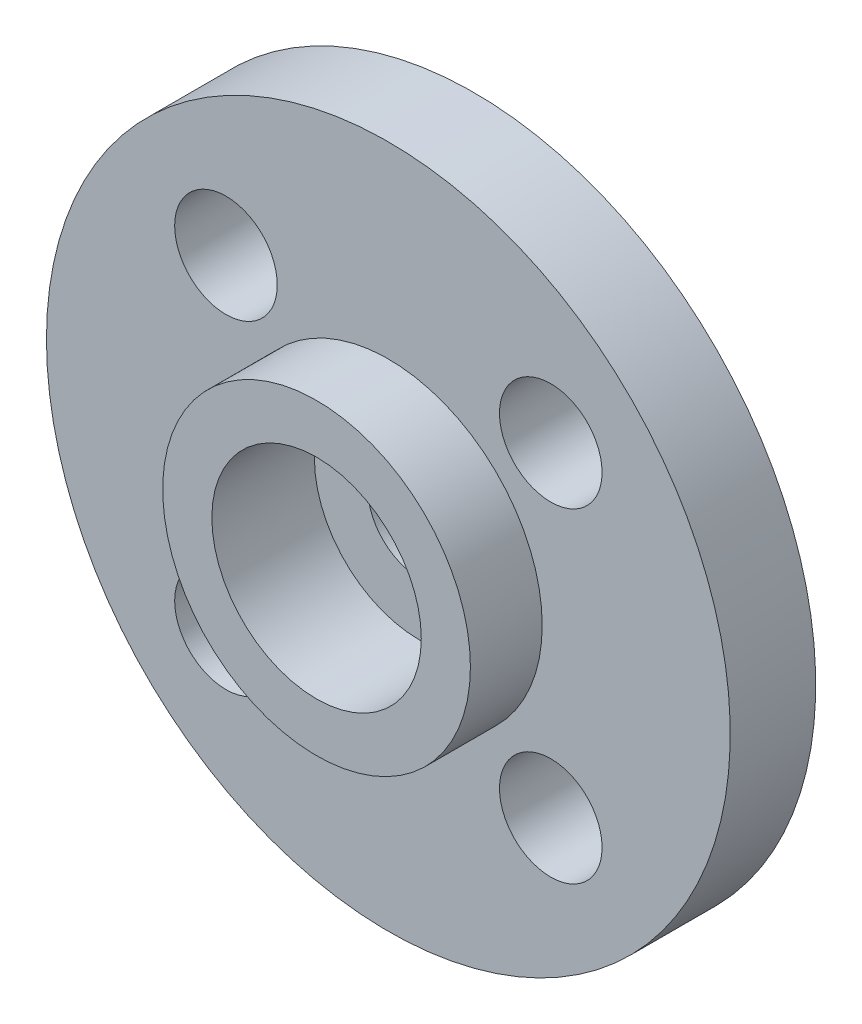
SolidWorks part; units mm, degrees
material "Material"
ref_plane "Front Plane" through (0, 0, 0) normal (0, 0, 1) x (1, 0, 0)
ref_plane "Top Plane" through (0, 0, 0) normal (0, 1, 0) x (1, 0, 0)
ref_plane "Right Plane" through (0, 0, 0) normal (1, 0, 0) x (0, 0, -1)
ref_plane "Plane1" through (0, 0, 0) normal (0, -1, 0) x (1, 0, 0)
sketch "Sketch1" plane through (0, 0, 0) normal (0, -1, 0) x (1, 0, 0)
  line L0 (10, 2.5) -> (0, 2.5)
  line L1 (0, 2.5) -> (0, 0)
  line L2 (0, 0) -> (10, 0)
  line L3 (10, 0) -> (10, 2.5)
  line L4 (0, 2.5) -> (0, 0) construction
revolve "Revolve1" add sketch "Sketch1" angle 360 about L4
sketch "Sketch2" plane through (0, 0, 2.5) normal (0, 0, 1) x (1, 0, 0)
  circle A0 centre (0, 0) radius 4.5
extrude "Boss-Extrude1" add sketch "Sketch2" along normal blind 2.1
hole_wizard "Ø3.0 (3) Diameter Hole1" positions "Sketch4" profile "Sketch3" hole size "Ø3.0" standard "ANSI Metric"
sketch "Sketch4" plane through (0, 0, 0) normal (0, 0, -1) x (-1, 0, 0)
  point P0 (-4.75, -4.75)
  point P1 (4.75, -4.75)
  point P2 (4.75, 4.75)
  point P3 (-4.75, 4.75)
sketch "Sketch3" plane through (4.75, -4.75, 0) normal (1, 0, 0) x (0, 1, 0)
  line L0 (0, 0) -> (0, 4.6)
  line L1 (0, 4.6) -> (1.5, 4.6)
  line L2 (1.5, 4.6) -> (1.5, 0)
  line L5 (1.5, 0) -> (0, 0)
  line L11 (0, -6.35) -> (0, 107.95) construction
  dimension "Thru Hole Dia." = 3
  dimension "Thru Hole Depth" = 4.6
hole_wizard "CBORE for M2.5 Hex Head Machine Screw1" positions "Sketch6" profile "Sketch5" counterbore size "M2.5" standard "ANSI Metric"
sketch "Sketch6" plane through (0, 0, 4.6) normal (0, 0, 1) x (1, 0, 0)
  point P0 (0, 0)
sketch "Sketch5" plane through (0, 0, 4.6) normal (1, 0, 0) x (0, -1, 0)
  line L0 (0, 0) -> (0, 4.6)
  line L1 (0, 4.6) -> (1.5, 4.6)
  line L3 (1.5, 4.6) -> (1.5, 3)
  line L4 (1.5, 3) -> (3.063, 3)
  line L5 (3.063, 3) -> (3.063, 0)
  line L7 (3.063, 0) -> (0, 0)
  line L11 (0, -6.35) -> (0, 107.95) construction
  dimension "Thru Hole Dia." = 3
  dimension "Thru Hole Depth" = 4.6
  dimension "C'Bore Dia." = 6.1261
  dimension "C'Bore Depth" = 3
